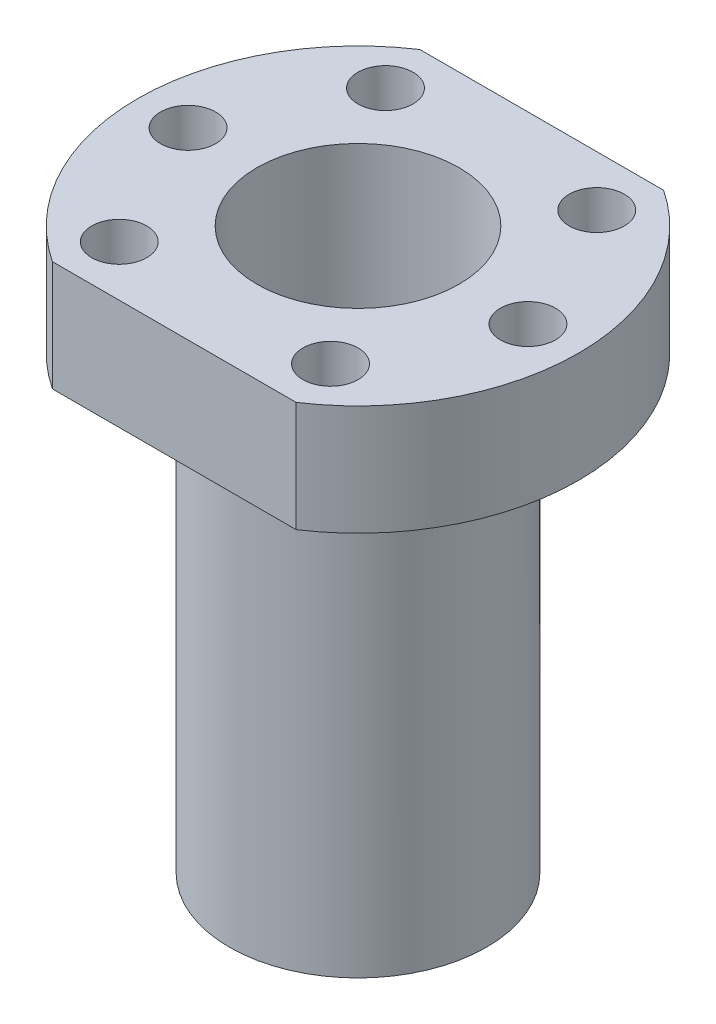
SolidWorks part; units mm, degrees
ref_plane "Front Plane" through (0, 0, 0) normal (0, 0, 1) x (1, 0, 0)
ref_plane "Top Plane" through (0, 0, 0) normal (0, 1, 0) x (1, 0, 0)
ref_plane "Right Plane" through (0, 0, 0) normal (1, 0, 0) x (0, 0, -1)
sketch "Sketch1" plane through (0, 0, 0) normal (0, 1, 0) x (1, 0, 0)
  line L1 (0, 20) -> (13.2665, 20)
  line L3 (13.2665, -20) -> (-13.2665, -20)
  line L5 (-13.2665, 20) -> (0, 20)
  arc A0 (-13.2665, 20) -> (-13.2665, -20) centre (0, 0) ccw
  arc A1 (13.2665, -20) -> (13.2665, 20) centre (0, 0) ccw
extrude "Boss-Extrude1" add sketch "Sketch1" along normal blind 12
sketch "Sketch2" plane through (0, 0, 0) normal (0, -1, 0) x (1, 0, 0)
  circle A0 centre (0, 0) radius 14
extrude "Boss-Extrude2" add sketch "Sketch2" along normal blind 49
sketch "Sketch3" plane through (0, 12, 0) normal (0, 1, 0) x (1, 0, 0)
  circle A0 centre (0, 0) radius 11
  circle A1 centre (-11.5, 14.4914) radius 3
  circle A2 centre (-18.5, 0) radius 3
  circle A3 centre (-11.5, -14.4914) radius 3
  circle A4 centre (11.5, -14.4914) radius 3
  circle A5 centre (18.5, 0) radius 3
  circle A6 centre (11.5, 14.4914) radius 3
extrude "Cut-Extrude1" cut sketch "Sketch3" against normal through all
